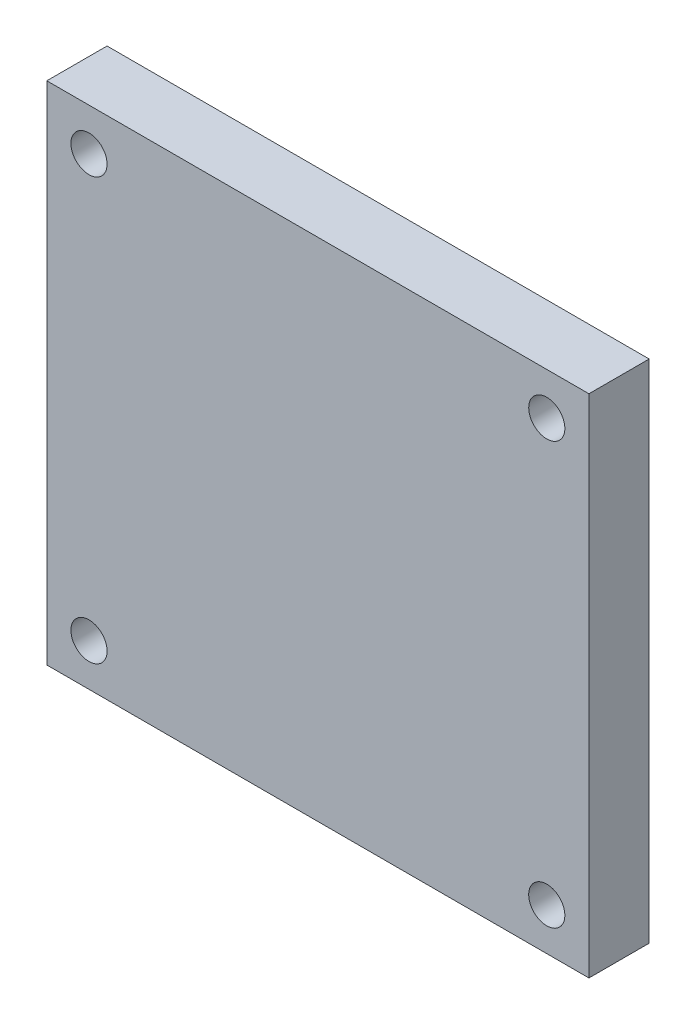
SolidWorks part; units mm, degrees
ref_plane "前视基准面" through (0, 0, 0) normal (0, 0, 1) x (1, 0, 0)
ref_plane "上视基准面" through (0, 0, 0) normal (0, 1, 0) x (1, 0, 0)
ref_plane "右视基准面" through (0, 0, 0) normal (1, 0, 0) x (0, 0, -1)
other "Configuration Table"
sketch "草图1" plane through (0, 0, 0) normal (0, 0, 1) x (1, 0, 0)
  line L0 (-45, 21) -> (32.4718, 21) construction
  line L1 (0, 0) -> (-45, 0)
  line L2 (0, 0) -> (0, 42)
  line L3 (0, 42) -> (-45, 42)
  line L4 (-45, 0) -> (-45, 42)
  line L5 (-22.5, 0) -> (-22.5, 27.4368) construction
  circle A0 centre (-3.5, 3.5) radius 1.5
  circle A1 centre (-41.5, 3.5) radius 1.5
  circle A2 centre (-3.5, 38.5) radius 1.5
  circle A3 centre (-41.5, 38.5) radius 1.5
  dimension "D3" = 3
  dimension "D4" = 3.5
  dimension "D5" = 3.5
  dimension "D1" = 45
  dimension "D2" = 42
extrude "凸台-拉伸1" add sketch "草图1" along normal blind 5
